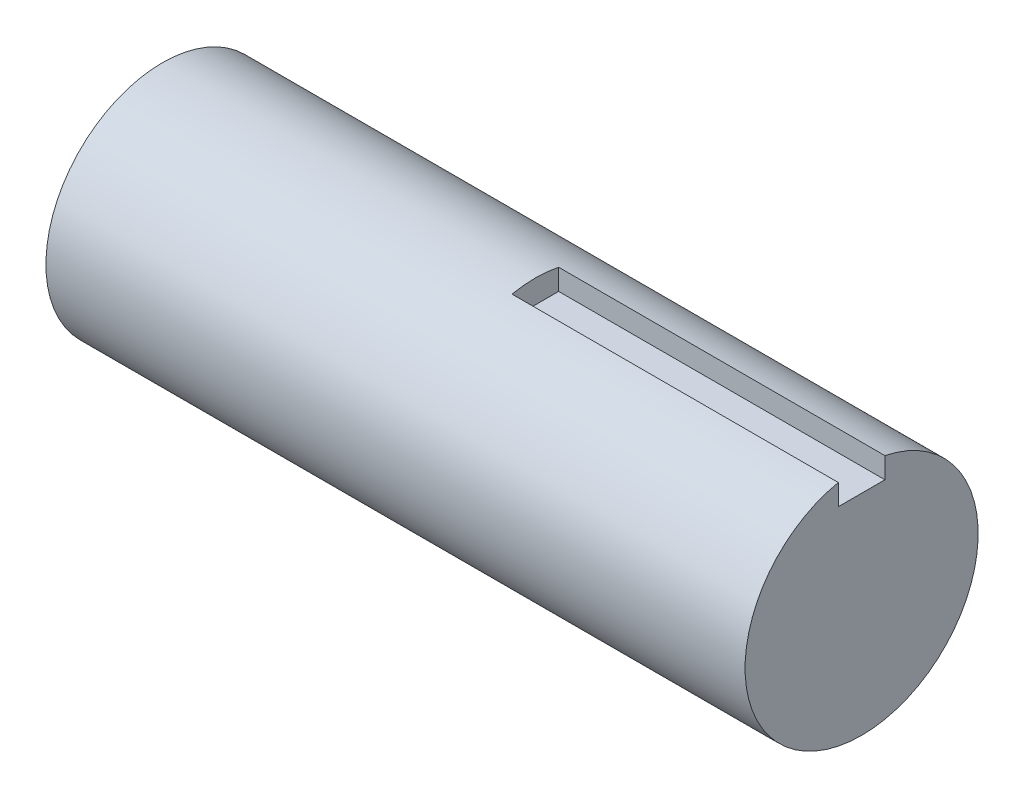
SolidWorks part; units mm, degrees
ref_plane "Front Plane" through (0, 0, 0) normal (0, 0, 1) x (1, 0, 0)
ref_plane "Top Plane" through (0, 0, 0) normal (0, 1, 0) x (1, 0, 0)
ref_plane "Right Plane" through (0, 0, 0) normal (1, 0, 0) x (0, 0, -1)
sketch "Sketch1" plane through (0, 0, 0) normal (1, 0, 0) x (0, 0, -1)
  circle A0 centre (0, 0) radius 25
  dimension "D1" = 50
extrude "Boss-Extrude1" add sketch "Sketch1" along normal blind 150
sketch "Sketch2" plane through (150, 0, 0) normal (1, 0, 0) x (0, 0, -1)
  line L0 (0, 0) -> (0, 20) construction
  line L5 (-5, 30) -> (5, 30)
  line L6 (-5, 30) -> (-5, 20)
  line L7 (-5, 20) -> (5, 20)
  line L8 (5, 30) -> (5, 20)
  line L9 (-5, 30) -> (5, 20) construction
  line L10 (-5, 20) -> (5, 30) construction
  circle A2 centre (0, 0) radius 25 construction
  point P0 (0, 25)
  dimension "D1" = 10
  dimension "D2" = 20
extrude "Cut-Extrude1" cut sketch "Sketch2" against normal blind 70
